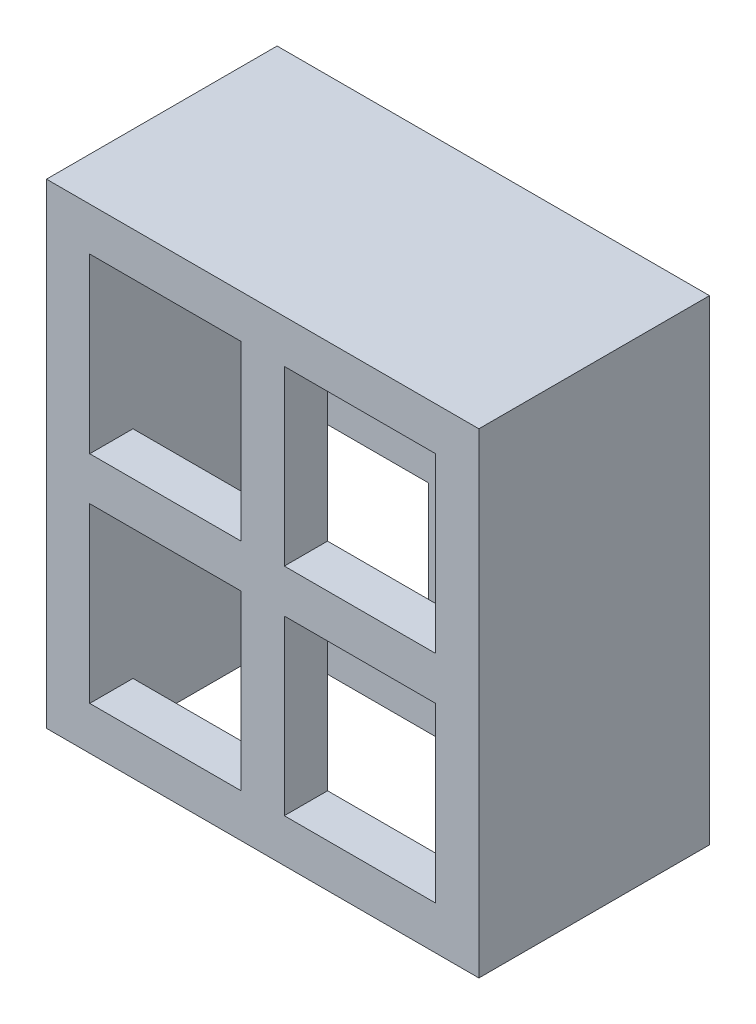
SolidWorks part; units mm, degrees
ref_plane "Front Plane" through (0, 0, 0) normal (0, 0, 1) x (1, 0, 0)
ref_plane "Top Plane" through (0, 0, 0) normal (0, 1, 0) x (1, 0, 0)
ref_plane "Right Plane" through (0, 0, 0) normal (1, 0, 0) x (0, 0, -1)
sketch "Sketch1" plane through (0, 0, 0) normal (0, 1, 0) x (1, 0, 0)
  line L1 (-33.8492, -24.1983) -> (-18.8492, -24.1983)
  line L2 (-33.8492, -24.1983) -> (-33.8492, -16.1983)
  line L3 (-33.8492, -16.1983) -> (-18.8492, -16.1983)
  line L4 (-18.8492, -24.1983) -> (-18.8492, -16.1983)
  dimension "D1" = 15
  dimension "D2" = 8
extrude "Boss-Extrude2" add sketch "Sketch1" along normal blind 18
sketch "Sketch2" plane through (0, 0, 0) normal (0, -1, 0) x (-1, 0, 0)
  line L0 (18.8492, -24.1983) -> (18.8492, -16.1983) construction
  line L1 (32.3492, -22.6983) -> (20.3492, -22.6983)
  line L2 (32.3492, -22.6983) -> (32.3492, -17.6983)
  line L3 (32.3492, -17.6983) -> (20.3492, -17.6983)
  line L4 (20.3492, -22.6983) -> (20.3492, -17.6983)
  line L5 (18.8492, -16.1983) -> (33.8492, -16.1983) construction
  line L6 (33.8492, -24.1983) -> (18.8492, -24.1983) construction
  line L7 (33.8492, -16.1983) -> (33.8492, -24.1983) construction
  dimension "D1" = 1.5
  dimension "D2" = 1.5
  dimension "D3" = 1.5
  dimension "D4" = 1.5
extrude "Cut-Extrude1" cut sketch "Sketch2" against normal blind 16.5
sketch "Sketch3" plane through (0, 0, 24.1983) normal (0, 0, 1) x (1, 0, 0)
  line L0 (-33.8492, 18) -> (-18.8492, 18) construction
  line L1 (-32.3492, 16.5) -> (-27.0992, 16.5)
  line L2 (-32.3492, 16.5) -> (-32.3492, 10.5)
  line L3 (-32.3492, 10.5) -> (-27.0992, 10.5)
  line L4 (-27.0992, 16.5) -> (-27.0992, 10.5)
  line L5 (-25.5992, 16.5) -> (-20.3492, 16.5)
  line L6 (-25.5992, 16.5) -> (-25.5992, 10.5)
  line L7 (-25.5992, 10.5) -> (-20.3492, 10.5)
  line L8 (-20.3492, 16.5) -> (-20.3492, 10.5)
  line L9 (-25.5992, 9) -> (-20.3492, 9)
  line L10 (-25.5992, 9) -> (-25.5992, 3)
  line L11 (-25.5992, 3) -> (-20.3492, 3)
  line L12 (-20.3492, 9) -> (-20.3492, 3)
  line L13 (-32.3492, 9) -> (-27.0992, 9)
  line L14 (-32.3492, 9) -> (-32.3492, 3)
  line L15 (-32.3492, 3) -> (-27.0992, 3)
  line L16 (-27.0992, 9) -> (-27.0992, 3)
  line L17 (-18.8492, 18) -> (-18.8492, 0) construction
  line L18 (-33.8492, 0) -> (-18.8492, 0) construction
  line L19 (-33.8492, 18) -> (-33.8492, 0) construction
  dimension "D1" = 1.5
  dimension "D2" = 1.5
  dimension "D3" = 1.5
  dimension "D4" = 1.5
  dimension "D5" = 3
  dimension "D6" = 3
  dimension "D7" = 1.5
  dimension "D8" = 1.5
  dimension "D9" = 1.5
  dimension "D10" = 1.5
  dimension "D11" = 1.5
  dimension "D12" = 1.5
  dimension "D13" = 5.25
  dimension "D14" = 5.25
  dimension "D15" = 6
  dimension "D16" = 6
extrude "Cut-Extrude2" cut sketch "Sketch3" against normal blind 8
sketch "Sketch4" plane through (0, 0, 24.1983) normal (0, 0, 1) x (1, 0, 0)
  line L0 (-33.8492, 0) -> (-18.8492, 0) construction
  line L1 (-32.3492, 1.5) -> (-27.0992, 1.5)
  line L2 (-32.3492, 1.5) -> (-32.3492, 0)
  line L3 (-32.3492, 0) -> (-27.0992, 0)
  line L4 (-27.0992, 1.5) -> (-27.0992, 0)
  line L5 (-33.8492, 18) -> (-33.8492, 0) construction
  line L6 (-25.5992, 1.5) -> (-20.3492, 1.5)
  line L7 (-25.5992, 1.5) -> (-25.5992, 0)
  line L8 (-25.5992, 0) -> (-20.3492, 0)
  line L9 (-20.3492, 1.5) -> (-20.3492, 0)
  line L10 (-18.8492, 18) -> (-18.8492, 0) construction
  dimension "D1" = 1.5
  dimension "D2" = 1.5
  dimension "D3" = 1.5
  dimension "D4" = 1.5
  dimension "D5" = 1.5
  dimension "D6" = 5.25
sketch "Sketch5" plane through (-18.8492, 0, 0) normal (1, 0, 0) x (0, 0, -1)
  line L0 (-24.1983, 0) -> (-16.1983, 0) construction
  line L1 (-22.6983, 1.5) -> (-17.6983, 1.5)
  line L2 (-22.6983, 1.5) -> (-22.6983, 0)
  line L3 (-22.6983, 0) -> (-17.6983, 0)
  line L4 (-17.6983, 1.5) -> (-17.6983, 0)
  line L5 (-24.1983, 1.5) -> (-24.1983, 0) construction
  line L6 (-16.1983, 18) -> (-16.1983, 0) construction
  dimension "D1" = 1.5
  dimension "D2" = 1.5
  dimension "D3" = 1.5
extrude "Cut-Extrude3" cut sketch "Sketch5" against normal blind 15
extrude "Cut-Extrude4" cut sketch "Sketch4" against normal blind 15
sketch "Sketch6" plane through (0, 0, 0) normal (0, -1, 0) x (1, 0, 0)
  line L1 (-18.8492, 24.1983) -> (-33.8492, 24.1983)
  line L2 (-18.8492, 24.1983) -> (-18.8492, 16.1983)
  line L3 (-18.8492, 16.1983) -> (-33.8492, 16.1983)
  line L4 (-33.8492, 24.1983) -> (-33.8492, 16.1983)
extrude "Cut-Extrude5" cut sketch "Sketch6" against normal blind 1.5
